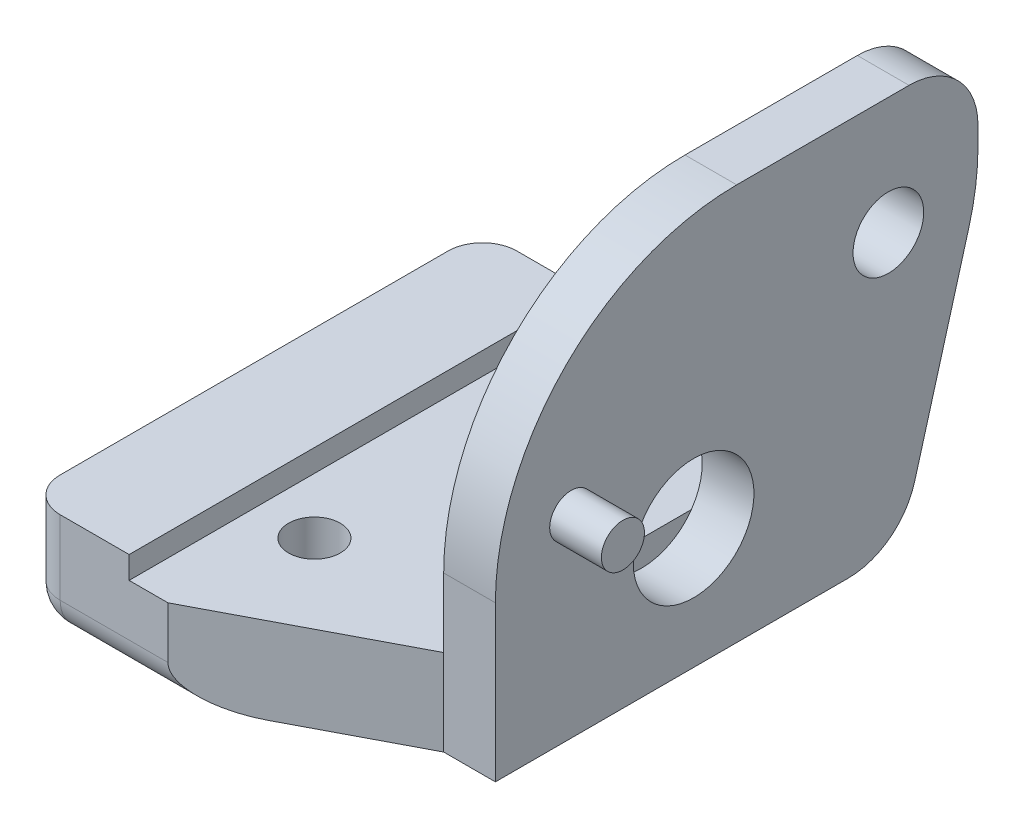
SolidWorks part; units mm, degrees
ref_plane "前视基准面" through (0, 0, 0) normal (0, 0, 1) x (1, 0, 0)
ref_plane "上视基准面" through (0, 0, 0) normal (0, 1, 0) x (1, 0, 0)
ref_plane "右视基准面" through (0, 0, 0) normal (1, 0, 0) x (0, 0, -1)
other "Configuration Table"
sketch "草图1" plane through (0, 0, 0) normal (0, 1, 0) x (1, 0, 0)
  line L0 (0, 0) -> (8.25, 0)
  line L1 (0, 0) -> (0, 26.5)
  line L2 (0, 26.5) -> (18.75, 26.5)
  line L3 (18.75, 26.5) -> (18.75, 5.5)
  line L4 (18.75, 5.5) -> (8.25, 0)
  dimension "D1" = 8.25
  dimension "D2" = 26.5
  dimension "D3" = 18.75
  dimension "D4" = 21
extrude "凸台-拉伸1" add sketch "草图1" against normal blind 5
sketch "草图2" plane through (18.75, 0, 0) normal (1, 0, 0) x (0, 0, -1)
  line L0 (5.5, -5) -> (5.5, 18)
  line L1 (5.5, 18) -> (33.5, 18)
  line L2 (33.5, 18) -> (33.5, -5)
  line L3 (33.5, -5) -> (5.5, -5)
  dimension "D1" = 28
  dimension "D2" = 23
extrude "凸台-拉伸2" add sketch "草图2" along normal blind 3
sketch "草图3" plane through (0, 0, 0) normal (0, 1, 0) x (1, 0, 0)
  line L0 (18.75, 26.5) -> (0, 26.5) construction
  line L1 (18.75, 33.5) -> (18.75, 5.5) construction
  line L3 (9.5, 26.5) -> (9.5, 0.6548) construction
  line L4 (8.25, 0) -> (18.75, 5.5) construction
  circle A0 centre (9.25, 22.5) radius 1.5
  circle A1 centre (9.25, 7.5) radius 1.5
  dimension "D1" = 3
  dimension "D2" = 3
  dimension "D3" = 4
  dimension "D4" = 9.5
  dimension "D5" = 15
extrude "切除-拉伸1" cut sketch "草图3" against normal through all
sketch "草图4" plane through (18.75, 0, 0) normal (-1, 0, 0) x (0, 0, 1)
  line L0 (-26.5, -5) -> (0, -5) construction
  line L5 (-26.5, -5) -> (-26.5, 0) construction
  circle A0 centre (-17, 2) radius 3.5
  circle A1 centre (-9.9, 6.2) radius 1.25
  dimension "D1" = 7
  dimension "D3" = 7
  dimension "D2" = 9.5
  dimension "D5" = 2.5
extrude "切除-拉伸2" cut sketch "草图4" against normal through all
fillet "圆角3" radius 14 1 edges at (20.25, 18, -5.5)
fillet "圆角4" radius 2 1 edges at (9.375, -5, -26.5)
sketch "草图6" plane through (0, 0, 0) normal (0, 1, 0) x (1, 0, 0)
  line L0 (0, 26.5) -> (6, 26.5)
  line L1 (18.75, 26.5) -> (0, 26.5) construction
  line L2 (6, 26.5) -> (6, 0)
  line L3 (0, 0) -> (8.25, 0) construction
  line L4 (6, 0) -> (0, 0)
  line L5 (0, 0) -> (0, 26.5)
extrude "凸台-拉伸3" add sketch "草图6" along normal blind 1.3
fillet "圆角5" radius 2 1 edges at (0, -1.85, 0)
fillet "圆角6" radius 2 5 edges at (0, -0.85, -26.5) (0, -5, -13.25) (0, -4.4142, -25.9142) (5.125, -5, 0) (0.5858, -5, -0.5858)
sketch "草图7" plane through (18.75, 0, 0) normal (-1, 0, 0) x (0, 0, 1)
  circle A0 centre (-9.9, 6.2) radius 1.25
extrude "凸台-拉伸4" add sketch "草图7" against normal blind 6
sketch "草图8" plane through (18.75, 0, 0) normal (-1, 0, 0) x (0, 0, 1)
  line L0 (-22.5, 18) -> (-33.5, 18)
  line L1 (-33.5, 18) -> (-33.5, 21.2)
  line L2 (-33.5, 21.2) -> (-22.5, 21.2)
  line L3 (-22.5, 21.2) -> (-22.5, 18)
  line L4 (-33.5, 18) -> (-19.5, 18) construction
extrude "凸台-拉伸5" add sketch "草图8" against normal blind 3
sketch "草图10" plane through (18.75, 0, 0) normal (-1, 0, 0) x (0, 0, 1)
  circle A7 centre (-28.3, 11.203) radius 2.05
  point P0 (-28.3, 18.203)
  point P3 (-28.3, 18.203)
  dimension "D1" = 4.1
extrude "切除-拉伸3" cut sketch "草图10" against normal blind 3
sketch "草图11" plane through (18.75, 0, 0) normal (-1, 0, 0) x (0, 0, 1)
  line L4 (-32.9771, 9.1408) -> (-29.8204, -2.083)
  line L5 (-33.5, 12.9313) -> (-33.5, -5)
  line L6 (-33.5, -5) -> (-25.9698, -5)
  arc A0 (-29.8204, -2.083) -> (-25.9698, -5) centre (-25.9698, -1) ccw
  arc A1 (-32.9771, 9.1408) -> (-33.5, 12.9313) centre (-19.5, 12.9313) cw
  dimension "D2" = 4
  dimension "D3" = 14
  dimension "D1" = 17.9313
  dimension "D4" = 7.5302
extrude "切除-拉伸4" cut sketch "草图11" against normal blind 3
fillet "圆角7" radius 1 1 edges at (20.25, 18, -22.5)
fillet "圆角8" radius 2 1 edges at (20.25, 21.2, -22.5)
fillet "圆角9" radius 2 1 edges at (20.25, 21.2, -33.5)
sketch "草图12" plane through (18.75, 0, 0) normal (-1, 0, 0) x (0, 0, 1)
  line L0 (-21.5, 18) -> (-33.5, 18)
  line L1 (-33.5, 12.9313) -> (-33.5, 19.2) construction
  line L2 (-33.5, 18) -> (-36.9512, 21.9337)
  line L3 (-36.9512, 21.9337) -> (-20.7902, 21.9337)
  line L4 (-20.7902, 21.9337) -> (-21.5, 18)
extrude "切除-拉伸5" cut sketch "草图12" against normal blind 10
fillet "圆角10" radius 4 1 edges at (20.25, 18, -33.5)
